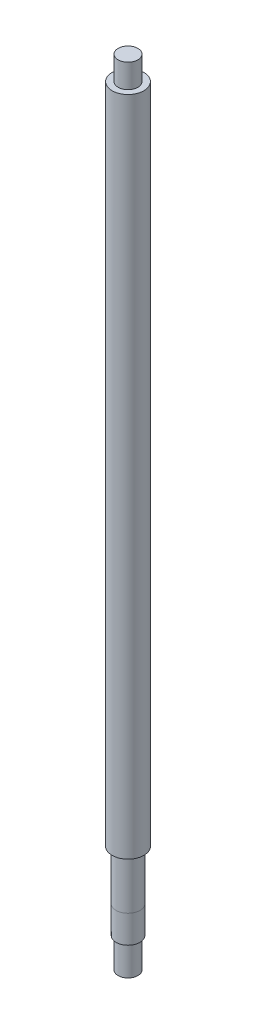
SolidWorks part; units mm, degrees
ref_plane "Front Plane" through (0, 0, 0) normal (0, 0, 1) x (1, 0, 0)
ref_plane "Top Plane" through (0, 0, 0) normal (0, 1, 0) x (1, 0, 0)
ref_plane "Right Plane" through (0, 0, 0) normal (1, 0, 0) x (0, 0, -1)
ref_plane "Plane1"
sketch "Sketch1" plane through (0, 0, 0) normal (0, 1, 0) x (-1, 0, 0)
  circle A0 centre (0, 0) radius 8
  dimension "D1" = 16
extrude "Extrusion1" add sketch "Sketch1" along normal blind 400
sketch "Sketch2" plane through (0, 0, 0) normal (0, -1, 0) x (1, 0, 0)
  circle A0 centre (0, 0) radius 8
extrude "Extrusion2" cut sketch "Sketch2" against normal blind 50
sketch "Sketch3" plane through (0, 50, 0) normal (0, -1, 0) x (1, 0, 0)
  circle A0 centre (0, 0) radius 8
extrude "Extrusion3" add sketch "Sketch3" along normal blind 50
sketch "Sketch4" plane through (0, 0, 0) normal (0, -1, 0) x (1, 0, 0)
  circle A0 centre (0, 0) radius 8
  circle A1 centre (0, 0) radius 6
  circle M1 centre (0, 0) radius 8
  dimension "D1" = 12
extrude "Thread1" cut sketch "Sketch4" against normal blind 14 contours A1 M1
cosmetic thread "Cosmetic Thread1" parameters "D2"=0
ref_plane "Plane2"
sketch "Sketch5" plane through (0, 14, 0) normal (0, -1, 0) x (1, 0, 0)
  circle A0 centre (0, 0) radius 8
  circle A1 centre (0, 0) radius 6.05
  dimension "D1" = 12.1
extrude "Extrusion5" cut sketch "Sketch5" against normal blind 25 contours A0 A1
sketch "Sketch6" plane through (0, 0, 0) normal (0, -1, 0) x (1, 0, 0)
  circle A0 centre (0, 0) radius 5
  dimension "D1" = 10
extrude "Extrusion6" add sketch "Sketch6" along normal blind 15
sketch "Sketch7" plane through (0, 400, 0) normal (0, 1, 0) x (-1, 0, 0)
  circle A0 centre (0, 0) radius 8
extrude "Extrusion7" cut sketch "Sketch7" against normal blind 27.101
sketch "Sketch8" plane through (0, 372.899, 0) normal (0, 1, 0) x (-1, 0, 0)
  circle A0 centre (0, 0) radius 5
  dimension "D1" = 10
extrude "Extrusion8" add sketch "Sketch8" along normal blind 12
